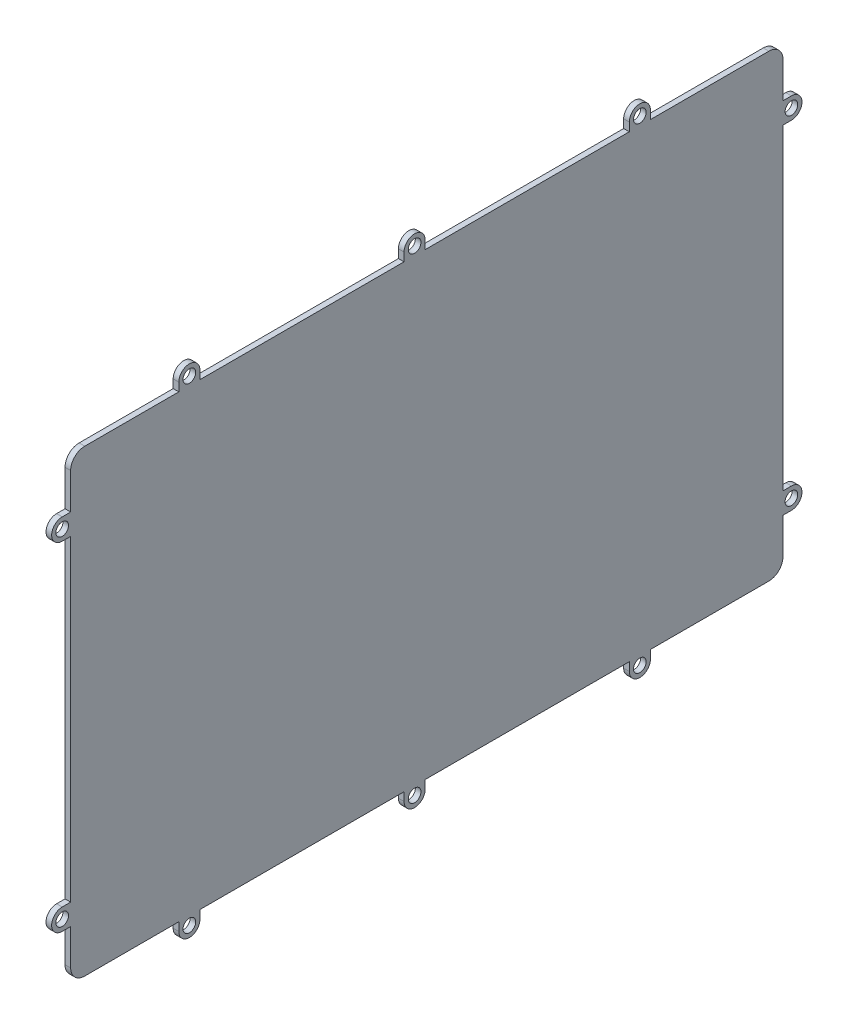
SolidWorks part; units mm, degrees
ref_plane "Ön Düzlem" through (0, 0, 0) normal (1, 0, 0) x (0, 1, 0)
ref_plane "Üst Düzlem" through (0, 0, 0) normal (0, 0, 1) x (0, 1, 0)
ref_plane "Sağ Düzlem" through (0, 0, 0) normal (0, 1, 0) x (-1, 0, 0)
sketch "Çizim2" plane through (0, 0, 0) normal (1, 0, 0) x (0, 1, 0)
  line L0 (-77.0993, -127.8484) -> (-64.3493, -127.8484)
  line L1 (-64.3493, -127.8484) -> (-64.3493, -130.8484)
  line L2 (-56.8493, -130.8484) -> (-56.8493, -127.8484)
  line L3 (-56.8493, -127.8484) -> (55.6507, -127.8484)
  line L4 (55.6507, -127.8484) -> (55.6507, -130.8484)
  line L5 (63.1507, -130.8484) -> (63.1507, -127.8484)
  line L6 (63.1507, -127.8484) -> (75.9007, -127.8484)
  line L7 (80.9007, -122.8484) -> (80.9007, -80.7645)
  line L8 (80.9007, -80.7645) -> (83.9007, -80.7645)
  line L9 (83.9007, -73.2645) -> (80.9007, -73.2645)
  line L10 (80.9007, -73.2645) -> (80.9007, -0.7645)
  line L11 (80.9007, -0.7645) -> (83.9007, -0.7645)
  line L12 (83.9007, 6.7355) -> (80.9007, 6.7355)
  line L13 (80.9007, 6.7355) -> (80.9007, 79.2355)
  line L14 (80.9007, 79.2355) -> (83.9007, 79.2355)
  line L15 (83.9007, 86.7355) -> (80.9007, 86.7355)
  line L16 (80.9007, 86.7355) -> (80.9007, 120.1516)
  line L17 (75.9007, 125.1516) -> (63.1507, 125.1516)
  line L18 (63.1507, 125.1516) -> (63.1507, 128.1516)
  line L19 (55.6507, 128.1516) -> (55.6507, 125.1516)
  line L20 (55.6507, 125.1516) -> (-56.8493, 125.1516)
  line L21 (-56.8493, 125.1516) -> (-56.8493, 128.1516)
  line L22 (-64.3493, 128.1516) -> (-64.3493, 125.1516)
  line L23 (-64.3493, 125.1516) -> (-77.0993, 125.1516)
  line L24 (-82.0993, 120.1516) -> (-82.0993, 86.7355)
  line L25 (-82.0993, 86.7355) -> (-85.0993, 86.7355)
  line L26 (-85.0993, 79.2355) -> (-82.0993, 79.2355)
  line L27 (-82.0993, 79.2355) -> (-82.0993, 6.7355)
  line L28 (-82.0993, 6.7355) -> (-85.0993, 6.7355)
  line L29 (-85.0993, -0.7645) -> (-82.0993, -0.7645)
  line L30 (-82.0993, -0.7645) -> (-82.0993, -73.2645)
  line L31 (-82.0993, -73.2645) -> (-85.0993, -73.2645)
  line L32 (-85.0993, -80.7645) -> (-82.0993, -80.7645)
  line L33 (-82.0993, -80.7645) -> (-82.0993, -122.8484)
  circle A0 centre (-85.0993, 82.9855) radius 1.6
  circle A1 centre (-85.0993, 2.9855) radius 1.6
  circle A2 centre (-85.0993, -77.0145) radius 1.6
  circle A3 centre (-60.5993, -130.8484) radius 1.6
  arc A4 (-82.0993, -122.8484) -> (-77.0993, -127.8484) centre (-77.0993, -122.8484) ccw
  arc A5 (-64.3493, -130.8484) -> (-56.8493, -130.8484) centre (-60.5993, -130.8484) ccw
  arc A6 (55.6507, -130.8484) -> (63.1507, -130.8484) centre (59.4007, -130.8484) ccw
  arc A7 (75.9007, -127.8484) -> (80.9007, -122.8484) centre (75.9007, -122.8484) ccw
  arc A8 (83.9007, -80.7645) -> (83.9007, -73.2645) centre (83.9007, -77.0145) ccw
  arc A9 (83.9007, -0.7645) -> (83.9007, 6.7355) centre (83.9007, 2.9855) ccw
  arc A10 (83.9007, 79.2355) -> (83.9007, 86.7355) centre (83.9007, 82.9855) ccw
  arc A11 (80.9007, 120.1516) -> (75.9007, 125.1516) centre (75.9007, 120.1516) ccw
  arc A12 (63.1507, 128.1516) -> (55.6507, 128.1516) centre (59.4007, 128.1516) ccw
  arc A13 (-56.8493, 128.1516) -> (-64.3493, 128.1516) centre (-60.5993, 128.1516) ccw
  arc A14 (-77.0993, 125.1516) -> (-82.0993, 120.1516) centre (-77.0993, 120.1516) ccw
  arc A15 (-85.0993, 86.7355) -> (-85.0993, 79.2355) centre (-85.0993, 82.9855) ccw
  arc A16 (-85.0993, 6.7355) -> (-85.0993, -0.7645) centre (-85.0993, 2.9855) ccw
  arc A17 (-85.0993, -73.2645) -> (-85.0993, -80.7645) centre (-85.0993, -77.0145) ccw
  circle A18 centre (59.4007, -130.8484) radius 1.6
  circle A19 centre (83.9007, -77.0145) radius 1.6
  circle A20 centre (83.9007, 2.9855) radius 1.6
  circle A21 centre (83.9007, 82.9855) radius 1.6
  circle A22 centre (59.4007, 128.1516) radius 1.6
  circle A23 centre (-60.5993, 128.1516) radius 1.6
extrude "Yükseklik-Ekstrüzyon1" add sketch "Çizim2" along normal blind 2
sketch "Çizim3" plane through (2, 0, 0) normal (1, 0, 0) x (0, 1, 0)
  circle A0 centre (-60.5993, 128.1516) radius 2.25
  dimension "D1" = 4.5
extrude "Kes-Ekstrüzyon1" cut sketch "Çizim3" against normal blind 2
sketch "Çizim4" plane through (2, 0, 0) normal (1, 0, 0) x (0, 1, 0)
  point P0 (59.4007, 128.1516)
  point P1 (83.9007, 82.9855)
  point P3 (83.9007, 2.9855)
  point P5 (83.9007, -77.0145)
  point P7 (59.4007, -130.8484)
  point P9 (-60.5993, -130.8484)
  point P11 (-85.0993, -77.0145)
  point P13 (-85.0993, 2.9855)
  point P15 (-85.0993, 82.9855)
  point P17 (-207.9349, 192.7397)
pattern_sketch "Çizim-Çoğaltma1" of "Kes-Ekstrüzyon1" driven by "Çizim4"
